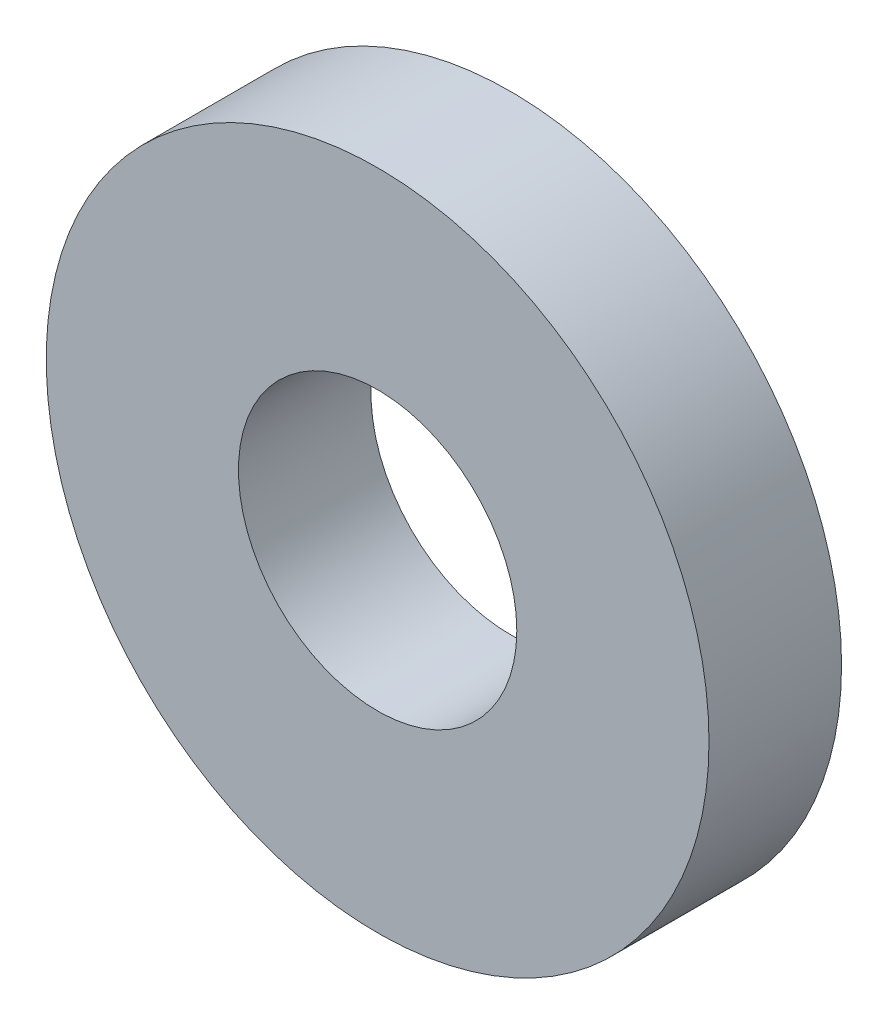
SolidWorks part; units mm, degrees
ref_plane "前视基准面" through (0, 0, 0) normal (0, 0, 1) x (1, 0, 0)
ref_plane "上视基准面" through (0, 0, 0) normal (0, 1, 0) x (1, 0, 0)
ref_plane "右视基准面" through (0, 0, 0) normal (1, 0, 0) x (0, 0, -1)
other "Configuration Table"
sketch "草图1" plane through (0, 0, 0) normal (0, 0, 1) x (1, 0, 0)
  circle A0 centre (0, 0) radius 2.1
  circle A1 centre (0, 0) radius 5
  dimension "D1" = 4.2
  dimension "D2" = 10
extrude "凸台-拉伸1" add sketch "草图1" along normal blind 2
